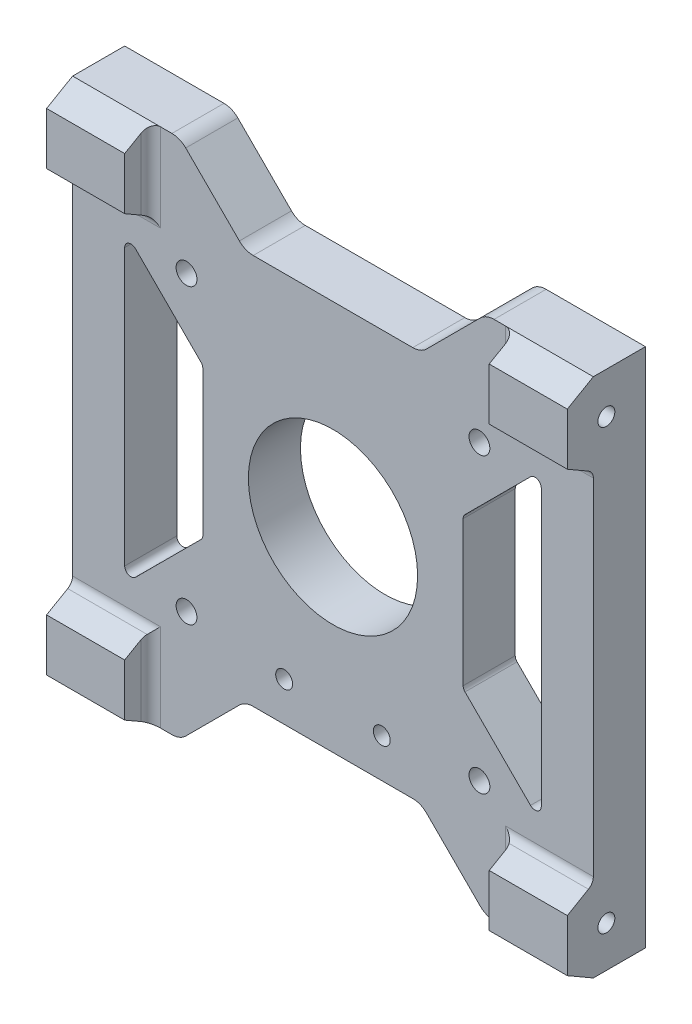
SolidWorks part; units mm, degrees
material "AISI 304"
ref_plane "前视基准面" through (0, 0, 0) normal (0, 0, 1) x (1, 0, 0)
ref_plane "上视基准面" through (0, 0, 0) normal (0, 1, 0) x (1, 0, 0)
ref_plane "右视基准面" through (0, 0, 0) normal (1, 0, 0) x (0, 0, -1)
sketch "草图1" plane through (0, 0, 0) normal (0, 0, 1) x (1, 0, 0)
  line L1 (-40, 40) -> (40, 40)
  line L2 (-40, 40) -> (-40, -40)
  line L3 (-40, -40) -> (40, -40)
  line L4 (40, 40) -> (40, -40)
  line L5 (-40, 40) -> (40, -40) construction
  line L6 (-40, -40) -> (40, 40) construction
  point P0 (0, 0)
  dimension "D1" = 80
  dimension "D2" = 80
extrude "凸台-拉伸1" add sketch "草图1" along normal blind 8
sketch "草图6" plane through (0, 0, 8) normal (0, 0, 1) x (1, 0, 0)
  circle A0 centre (0, 0) radius 13
  dimension "D1" = 26
extrude "切除-拉伸3" cut sketch "草图6" against normal blind 50
sketch "草图7" plane through (-40, 0, 0) normal (-1, 0, 0) x (0, 0, 1)
  line L0 (0, 0) -> (8, 0) construction
  line L1 (0, 40) -> (0, -40) construction
  line L2 (8, 40) -> (8, -40) construction
  line L3 (8, 40) -> (8, 27.3812)
  line L4 (8, 27.3812) -> (12, 29.6906)
  line L5 (12, 29.6906) -> (12, 37.6906)
  line L6 (12, 37.6906) -> (8, 40)
  line L7 (12, -37.6906) -> (8, -40)
  line L8 (12, -29.6906) -> (12, -37.6906)
  line L9 (8, -27.3812) -> (12, -29.6906)
  line L10 (8, -40) -> (8, -27.3812)
  dimension "D1" = 4
  dimension "D2" = 60
  dimension "D3" = 60
  dimension "D4" = 8
extrude "凸台-拉伸2" add sketch "草图7" against normal blind 12
fillet "圆角1" radius 1.5 4 edges at (-34, 27.3812, 8) (-28, 33.6906, 8) (-28, -33.6906, 8) (-34, -27.3812, 8)
mirror "镜向1" about plane through (0, 0, 0) normal (1, 0, 0) of "圆角1", "凸台-拉伸2"
sketch "草图8" plane through (-40, 0, 0) normal (-1, 0, 0) x (0, 0, 1)
  line L0 (0, 40) -> (0, -40) construction
  circle A0 centre (6, 33.6906) radius 1.3
  circle A1 centre (6, -33.6906) radius 1.3
  dimension "D1" = 2.6
  dimension "D2" = 6
  dimension "D3" = 4
  dimension "D4" = 2.6
  dimension "D5" = 6
  dimension "D6" = 4
extrude "切除-拉伸4" cut sketch "草图8" against normal blind 10
mirror "镜向2" about plane through (0, 0, 0) normal (1, 0, 0) of "切除-拉伸4"
sketch "草图9" plane through (0, 0, 8) normal (0, 0, 1) x (1, 0, 0)
  circle A0 centre (7.5, -24) radius 1.3
  circle A1 centre (-7.5, -24) radius 1.3
  dimension "D1" = 2.6
  dimension "D2" = 2.6
extrude "切除-拉伸5" cut sketch "草图9" against normal blind 10
sketch "草图10" plane through (0, 0, 8) normal (0, 0, 1) x (1, 0, 0)
  line L1 (22.5, 22.5) -> (-22.5, 22.5) construction
  line L2 (22.5, 22.5) -> (22.5, -22.5) construction
  line L3 (22.5, -22.5) -> (-22.5, -22.5) construction
  line L4 (-22.5, 22.5) -> (-22.5, -22.5) construction
  line L5 (22.5, 22.5) -> (-22.5, -22.5) construction
  line L6 (22.5, -22.5) -> (-22.5, 22.5) construction
  circle A0 centre (22.5, -22.5) radius 1.6
  circle A1 centre (-22.5, -22.5) radius 1.6
  circle A2 centre (22.5, 22.5) radius 1.6
  circle A3 centre (-22.5, 22.5) radius 1.6
  point P0 (0, 0)
  dimension "D3" = 3.2
  dimension "D4" = 3.2
  dimension "D5" = 3.2
  dimension "D6" = 3.2
  dimension "D1" = 45
  dimension "D2" = 45
extrude "切除-拉伸6" cut sketch "草图10" against normal blind 10
sketch "草图11" plane through (0, 0, 8) normal (0, 0, 1) x (1, 0, 0)
  line L0 (-23.5, 40) -> (-14.3787, 30.8787)
  line L1 (26.5, 40) -> (-26.5, 40) construction
  line L2 (-12.2574, 30) -> (12.2574, 30)
  line L3 (14.3787, 30.8787) -> (23.5, 40)
  line L4 (-23.5, 40) -> (23.5, 40)
  line L6 (-32, 21.178) -> (-32, -21.178)
  line L10 (0, 0) -> (0, 10.1562) construction
  line L11 (0, 0) -> (-9.0051, 0) construction
  line L12 (-23.5, -40) -> (23.5, -40)
  line L13 (14.3787, -30.8787) -> (23.5, -40)
  line L14 (-12.2574, -30) -> (12.2574, -30)
  line L15 (-23.5, -40) -> (-14.3787, -30.8787)
  line L16 (-30.3474, -21.8626) -> (-20.2835, -11.7987)
  line L17 (-20, -11.1142) -> (-20, 11.1142)
  line L18 (-20.2835, 11.7987) -> (-30.3474, 21.8626)
  line L19 (-26.5, 26.5152) -> (-40, 26.5152) construction
  line L20 (-40, -26.5152) -> (-26.5, -26.5152) construction
  line L21 (-40, 26.5152) -> (-40, -26.5152) construction
  line L22 (20.2835, 11.7987) -> (30.3474, 21.8626)
  line L23 (20, -11.1142) -> (20, 11.1142)
  line L24 (30.3474, -21.8626) -> (20.2835, -11.7987)
  line L25 (32, 21.178) -> (32, -21.178)
  arc A0 (-20, 11.1142) -> (-20.2835, 11.7987) centre (-20.9681, 11.1142) ccw
  arc A1 (-20.2835, -11.7987) -> (-20, -11.1142) centre (-20.9681, -11.1142) ccw
  arc A2 (-32, -21.178) -> (-30.3474, -21.8626) centre (-31.0319, -21.178) ccw
  arc A3 (-32, 21.178) -> (-30.3474, 21.8626) centre (-31.0319, 21.178) cw
  arc A4 (32, 21.178) -> (30.3474, 21.8626) centre (31.0319, 21.178) ccw
  arc A5 (32, -21.178) -> (30.3474, -21.8626) centre (31.0319, -21.178) cw
  arc A6 (20.2835, -11.7987) -> (20, -11.1142) centre (20.9681, -11.1142) cw
  arc A7 (20, 11.1142) -> (20.2835, 11.7987) centre (20.9681, 11.1142) cw
  arc A8 (14.3787, -30.8787) -> (12.2574, -30) centre (12.2574, -33) ccw
  arc A9 (-12.2574, -30) -> (-14.3787, -30.8787) centre (-12.2574, -33) ccw
  arc A10 (12.2574, 30) -> (14.3787, 30.8787) centre (12.2574, 33) ccw
  arc A11 (-14.3787, 30.8787) -> (-12.2574, 30) centre (-12.2574, 33) ccw
  point P32 (-32, -23.5152)
  point P35 (-32, 23.5152)
  point P50 (13.5, -30)
  point P53 (-13.5, -30)
  point P56 (13.5, 30)
  point P59 (-13.5, 30)
  dimension "D12" = 0.9681
  dimension "D13" = 3
  dimension "D1" = 45
  dimension "D2" = 45
  dimension "D3" = 45
  dimension "D4" = 45
  dimension "D5" = 3
  dimension "D6" = 3
  dimension "D7" = 10
  dimension "D8" = 3
  dimension "D9" = 3
  dimension "D10" = 8
  dimension "D11" = 12
extrude "切除-拉伸7" cut sketch "草图11" against normal blind 10
fillet "圆角2" radius 3 4 edges at (23.5, -40, 4) (-23.5, -40, 4) (23.5, 40, 4) (-23.5, 40, 4)
